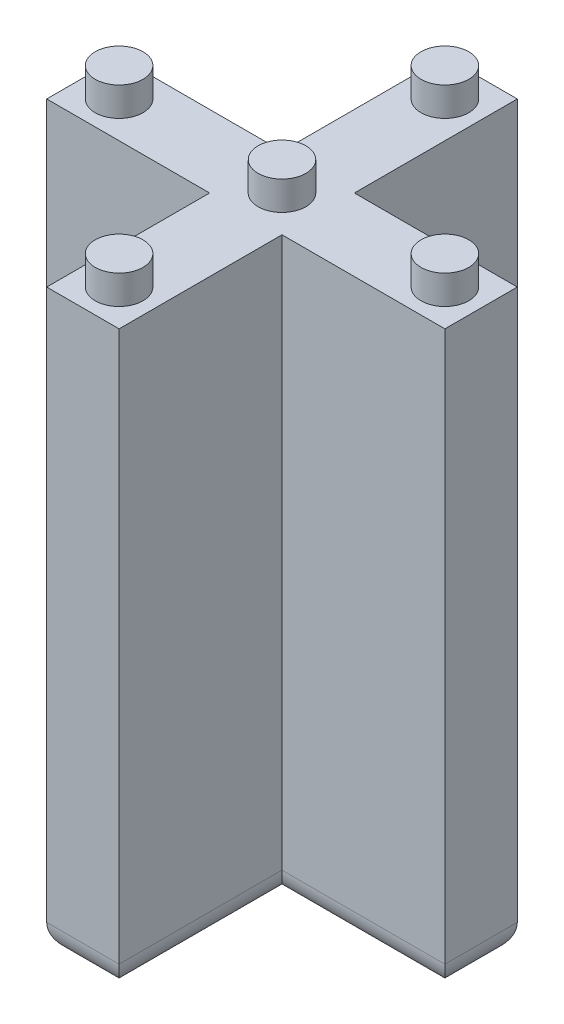
SolidWorks part; units mm, degrees
ref_plane "Front Plane" through (0, 0, 0) normal (0, 0, 1) x (1, 0, 0)
ref_plane "Top Plane" through (0, 0, 0) normal (0, 1, 0) x (1, 0, 0)
ref_plane "Right Plane" through (0, 0, 0) normal (1, 0, 0) x (0, 0, -1)
sketch "Sketch1" plane through (0, 0, 0) normal (0, 1, 0) x (1, 0, 0)
  line L1 (-2.5, -13.75) -> (2.5, -13.75)
  line L2 (-2.5, -13.75) -> (-2.5, -2.5)
  line L3 (-2.5, 13.75) -> (2.5, 13.75)
  line L4 (2.5, -13.75) -> (2.5, -2.5)
  line L7 (-13.75, -2.5) -> (-2.5, -2.5)
  line L8 (-13.75, -2.5) -> (-13.75, 2.5)
  line L9 (-13.75, 2.5) -> (-2.5, 2.5)
  line L10 (13.75, -2.5) -> (13.75, 2.5)
  line L15 (3.65, 0) -> (2.5, 0)
  line L16 (-55, 0) -> (55, 0) construction
  line L17 (2.5, -2.5) -> (13.75, -2.5)
  line L21 (2.5, 2.5) -> (13.75, 2.5)
  line L22 (-2.5, 2.5) -> (-2.5, 13.75)
  line L23 (2.5, -0.4545) -> (2.5, 0)
  line L24 (2.5, 2.5) -> (2.5, 13.75)
  point P0 (0, 0)
  point P6 (0, 0)
  dimension "D1" = 5
  dimension "D2" = 5
  dimension "D3" = 27.5
  dimension "D4" = 27.5
extrude "Boss-Extrude1" add sketch "Sketch1" along normal blind 40
sketch "Sketch2" plane through (0, 40, 0) normal (0, 1, 0) x (1, 0, 0)
  line L0 (0, 0) -> (0, 3.8481)
  line L1 (0, -15.125) -> (0, 15.125) construction
  line L2 (0, 3.8481) -> (0, 0)
  line L3 (0, 0) -> (2.8705, 0)
  line L4 (-15.125, 0) -> (15.125, 0) construction
  line L5 (13.75, 0) -> (11.25, 0)
  line L6 (13.75, -2.5) -> (13.75, 2.5) construction
  line L7 (-2.5, 13.75) -> (2.5, 13.75) construction
  circle A0 centre (11.25, 0) radius 1.65
  circle A1 centre (-11.25, 0) radius 1.65
  circle A2 centre (0, 11.25) radius 1.65
  circle A3 centre (0, -11.25) radius 1.65
  circle A4 centre (0, 0) radius 1.65
  dimension "D2" = 2.5
  dimension "D1" = 2.5
extrude "Boss-Extrude2" add sketch "Sketch2" along normal blind 2
fillet "Fillet2" radius 2 12 edges at (2.5, 0, -8.125) (0, 0, -13.75) (-2.5, 0, -8.125) (-8.125, 0, -2.5) (-13.75, 0, 0) (-8.125, 0, 2.5) (-2.5, 0, 8.125) (0, 0, 13.75) (2.5, 0, 8.125) (8.125, 0, 2.5) (13.75, 0, 0) (8.125, 0, -2.5)
